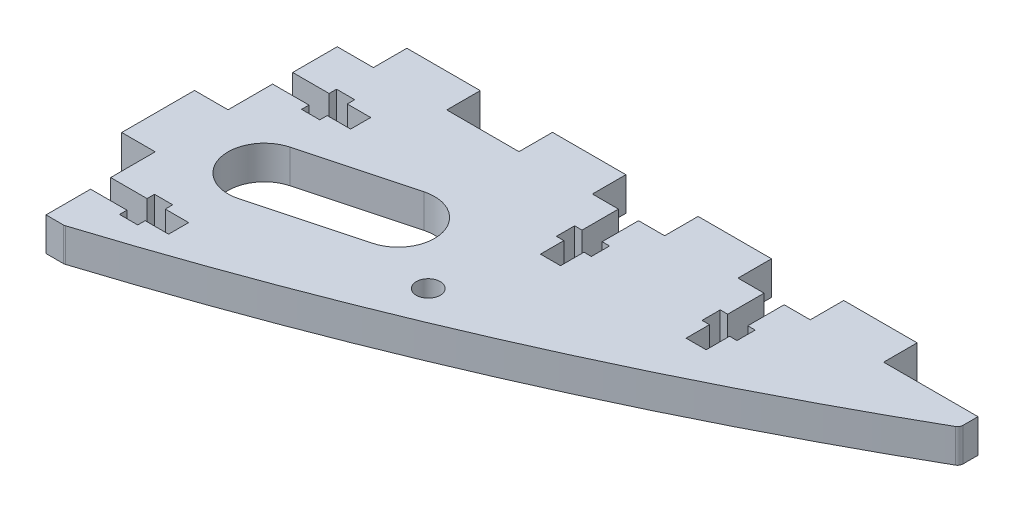
SolidWorks part; units mm, degrees
ref_plane "Front Plane" through (0, 0, 0) normal (0, 0, 1) x (1, 0, 0)
ref_plane "Top Plane" through (0, 0, 0) normal (0, 1, 0) x (1, 0, 0)
ref_plane "Right Plane" through (0, 0, 0) normal (1, 0, 0) x (0, 0, -1)
sketch "Sketch1" plane through (0, 0, 0) normal (0, 1, 0) x (1, 0, 0)
  line L0 (0, 0) -> (6.3, 0)
  line L1 (0, 0) -> (0, -19.05)
  line L2 (44.5, 5.842) -> (44.5, 0)
  line L3 (19.1, 5.842) -> (6.3, 5.842)
  line L4 (19.1, 5.842) -> (19.1, 0)
  line L5 (0, -50.8) -> (3.175, -50.8)
  line L6 (6.3, 5.842) -> (6.3, 0)
  line L7 (19.1, 5.842) -> (6.3, 0) construction
  line L8 (19.1, 0) -> (6.3, 5.842) construction
  line L9 (44.5, 0) -> (31.7, 5.842) construction
  line L10 (44.5, 5.842) -> (31.7, 0) construction
  line L11 (44.5, 5.842) -> (31.7, 5.842)
  line L12 (31.7, 5.842) -> (31.7, 0)
  line L13 (69.9, 5.842) -> (69.9, 0)
  line L14 (69.9, 0) -> (57.1, 5.842) construction
  line L15 (69.9, 5.842) -> (57.1, 0) construction
  line L16 (69.9, 5.842) -> (57.1, 5.842)
  line L17 (57.1, 5.842) -> (57.1, 0)
  line L18 (95.3, 5.842) -> (95.3, 0)
  line L19 (95.3, 0) -> (82.5, 5.842) construction
  line L20 (95.3, 5.842) -> (82.5, 0) construction
  line L21 (95.3, 5.842) -> (82.5, 5.842)
  line L22 (82.5, 5.842) -> (82.5, 0)
  line L23 (19.1, 0) -> (31.7, 0)
  line L24 (44.5, 0) -> (57.1, 0)
  line L25 (69.9, 0) -> (82.5, 0)
  line L26 (95.3, 0) -> (111.76, 0)
  line L27 (111.76, 0) -> (111.76, -3.175)
  line L28 (0, -25.4) -> (-11.5092, -25.4) construction
  line L29 (-5.842, -31.75) -> (0, -31.75)
  line L30 (-5.842, -31.75) -> (-5.842, -19.05)
  line L31 (-5.842, -19.05) -> (0, -19.05)
  line L33 (-5.842, -31.75) -> (0, -19.05) construction
  line L34 (-5.842, -19.05) -> (0, -31.75) construction
  line L35 (0, -31.75) -> (0, -50.8)
  spline S0 degree 2 poles (3.175, -50.8) (60.0368, -32.7718) (111.76, -3.175) knots 0 0 0 1 1 1
  point P4 (12.7, 2.921)
  point P24 (-2.921, -12.7)
  point P25 (-2.921, -25.4)
  dimension "D1" = 111.76
  dimension "D2" = 50.8
  dimension "D3" = 12.8
  dimension "D4" = 5.842
  dimension "D5" = 5.842
  dimension "D7" = 3.175
  dimension "D8" = 3.175
  dimension "D9" = 12.7
  dimension "D11" = 12.7
  dimension "D6" = 4
extrude "Boss-Extrude1" add sketch "Sketch1" along normal blind 5.842
sketch "Sketch3" plane through (0, 5.842, 0) normal (0, 1, 0) x (1, 0, 0)
  line L0 (12.7, -25.4136) -> (31.1009, -20.4831) construction
  line L1 (11.0565, -19.28) -> (29.4574, -14.3495)
  line L2 (14.3435, -31.5473) -> (32.7444, -26.6168)
  line L5 (12.7, -25.4136) -> (25.7792, -25.4136) construction
  line L6 (0, 0) -> (0, -19.05) construction
  arc A0 (11.0565, -19.28) -> (14.3435, -31.5473) centre (12.7, -25.4136) ccw
  arc A1 (32.7444, -26.6168) -> (29.4574, -14.3495) centre (31.1009, -20.4831) ccw
  point P2 (21.9004, -22.9484)
  dimension "D2" = 6.35
  dimension "D1" = 19.05
  dimension "D3" = 12.7
  dimension "D4" = 15
extrude "Cut-Extrude1" cut sketch "Sketch3" against normal through all
fillet "Fillet1" radius 1 2 edges at (3.175, 2.921, 50.8) (111.76, 2.921, 3.175)
sketch "Sketch4" plane through (0, 5.842, 0) normal (0, 1, 0) x (1, 0, 0)
  line L0 (50.8, 0) -> (50.8, -33.2938) construction
  line L1 (57.1, 0) -> (44.5, 0) construction
  line L2 (49.0474, -6.35) -> (47.752, -6.35)
  line L3 (49.0474, -9.525) -> (47.752, -9.525)
  line L4 (52.5526, -6.35) -> (52.5526, 0)
  line L5 (52.5526, 0) -> (49.0474, 0)
  line L6 (49.0474, -6.35) -> (49.0474, 0)
  line L7 (52.5526, -6.35) -> (49.0474, 0) construction
  line L8 (52.5526, 0) -> (49.0474, -6.35) construction
  line L9 (53.848, -9.525) -> (52.5526, -9.525)
  line L10 (53.848, -9.525) -> (53.848, -6.35)
  line L11 (53.848, -6.35) -> (52.5526, -6.35)
  line L12 (47.752, -9.525) -> (47.752, -6.35)
  line L13 (53.848, -9.525) -> (47.752, -6.35) construction
  line L14 (53.848, -6.35) -> (47.752, -9.525) construction
  line L15 (52.5526, -13.608) -> (49.0474, -13.608)
  line L16 (52.5526, -13.608) -> (52.5526, -9.525)
  line L17 (74.4474, -6.35) -> (73.152, -6.35)
  line L18 (49.0474, -13.608) -> (49.0474, -9.525)
  line L19 (52.5526, -13.608) -> (49.0474, -9.525) construction
  line L20 (52.5526, -9.525) -> (49.0474, -13.608) construction
  line L21 (74.4474, -9.525) -> (73.152, -9.525)
  line L22 (77.9526, -6.35) -> (77.9526, 0)
  line L23 (77.9526, 0) -> (74.4474, 0)
  line L24 (74.4474, -6.35) -> (74.4474, 0)
  line L25 (79.248, -9.525) -> (77.9526, -9.525)
  line L26 (79.248, -9.525) -> (79.248, -6.35)
  line L27 (79.248, -6.35) -> (77.9526, -6.35)
  line L28 (73.152, -9.525) -> (73.152, -6.35)
  line L29 (77.9526, -13.608) -> (74.4474, -13.608)
  line L30 (77.9526, -13.608) -> (77.9526, -9.525)
  line L31 (74.4474, -13.608) -> (74.4474, -9.525)
  line L32 (77.9526, -6.35) -> (74.4474, 0) construction
  line L33 (77.9526, 0) -> (74.4474, -6.35) construction
  line L34 (79.248, -9.525) -> (73.152, -6.35) construction
  line L35 (79.248, -6.35) -> (73.152, -9.525) construction
  line L36 (77.9526, -13.608) -> (74.4474, -9.525) construction
  line L37 (77.9526, -9.525) -> (74.4474, -13.608) construction
  line L38 (0, -9.525) -> (100.3581, -9.525) construction
  line L39 (0, 0) -> (0, -19.05) construction
  line L40 (0, -41.275) -> (30.9925, -41.275) construction
  line L41 (0, -31.75) -> (0, -50.8) construction
  line L42 (9.525, -7.7724) -> (9.525, -6.477)
  line L43 (6.35, -11.2776) -> (0, -11.2776)
  line L44 (-5.842, -25.4) -> (0, -25.4) construction
  line L45 (6.35, -7.7724) -> (0, -7.7724)
  line L46 (0, -11.2776) -> (0, -7.7724)
  line L47 (6.35, -11.2776) -> (0, -7.7724) construction
  line L48 (6.35, -7.7724) -> (0, -11.2776) construction
  line L49 (9.525, -12.573) -> (6.35, -12.573)
  line L50 (9.525, -12.573) -> (9.525, -11.2776)
  line L51 (9.525, -6.477) -> (6.35, -6.477)
  line L52 (6.35, -12.573) -> (6.35, -11.2776)
  line L53 (9.525, -12.573) -> (6.35, -6.477) construction
  line L54 (9.525, -6.477) -> (6.35, -12.573) construction
  line L55 (13.608, -11.2776) -> (9.525, -11.2776)
  line L56 (13.608, -11.2776) -> (13.608, -7.7724)
  line L57 (13.608, -7.7724) -> (9.525, -7.7724)
  line L58 (6.35, -7.7724) -> (6.35, -6.477)
  line L59 (13.608, -11.2776) -> (9.525, -7.7724) construction
  line L60 (13.608, -7.7724) -> (9.525, -11.2776) construction
  line L61 (-5.842, -19.05) -> (-5.842, -31.75) construction
  line L62 (13.608, -43.0276) -> (9.525, -39.5224) construction
  line L63 (13.608, -39.5224) -> (9.525, -43.0276) construction
  line L64 (9.525, -44.323) -> (6.35, -38.227) construction
  line L65 (9.525, -38.227) -> (6.35, -44.323) construction
  line L66 (6.35, -43.0276) -> (0, -39.5224) construction
  line L67 (6.35, -39.5224) -> (0, -43.0276) construction
  line L68 (6.35, -43.0276) -> (6.35, -44.323)
  line L69 (13.608, -43.0276) -> (9.525, -43.0276)
  line L70 (13.608, -39.5224) -> (13.608, -43.0276)
  line L71 (13.608, -39.5224) -> (9.525, -39.5224)
  line L72 (6.35, -38.227) -> (6.35, -39.5224)
  line L73 (9.525, -44.323) -> (6.35, -44.323)
  line L74 (9.525, -38.227) -> (9.525, -39.5224)
  line L75 (9.525, -38.227) -> (6.35, -38.227)
  line L76 (0, -39.5224) -> (0, -43.0276)
  line L77 (6.35, -43.0276) -> (0, -43.0276)
  line L78 (6.35, -39.5224) -> (0, -39.5224)
  line L79 (9.525, -43.0276) -> (9.525, -44.323)
  parabola Q0 (3.3227, -50.7532) -> (111.2558, -3.4632) focus (-51.5808, 224.913) apex (61.1285, -28.8307) construction
  parabola Q1 (3.3227, -50.7532) -> (111.2558, -3.4632) focus (-51.5808, 224.913) apex (61.1285, -28.8307) construction
  point P8 (50.8, -3.175)
  point P13 (50.8, -7.9375)
  point P18 (50.8, -11.5665)
  point P24 (76.2, -3.175)
  point P29 (76.2, -7.9375)
  point P34 (76.2, -11.5665)
  point P50 (3.175, -9.525)
  point P55 (7.9375, -9.525)
  point P60 (11.5665, -9.525)
  point P81 (11.5665, -41.275)
  point P82 (7.9375, -41.275)
  point P83 (3.175, -41.275)
  dimension "D1" = 3.5052
  dimension "D2" = 6.096
  dimension "D3" = 3.175
  dimension "D4" = 6.35
  dimension "D5" = 3.5052
  dimension "D6" = 4.083
  dimension "D8" = 3.5052
  dimension "D9" = 6.35
  dimension "D10" = 3.175
  dimension "D11" = 6.096
  dimension "D12" = 4.083
  dimension "D13" = 3.5052
  dimension "D7" = 2
extrude "Cut-Extrude2" cut sketch "Sketch4" against normal through all
sketch "Sketch5" plane through (0, 5.842, 0) normal (0, 1, 0) x (1, 0, 0)
  line L0 (49.0474, 0) -> (44.5, 0) construction
  line L1 (0, -11.2776) -> (0, -19.05) construction
  circle A0 centre (44.45, -28.575) radius 2.0828
  dimension "D1" = 4.1656
  dimension "D2" = 28.575
  dimension "D3" = 44.45
extrude "Cut-Extrude3" cut sketch "Sketch5" against normal through all
